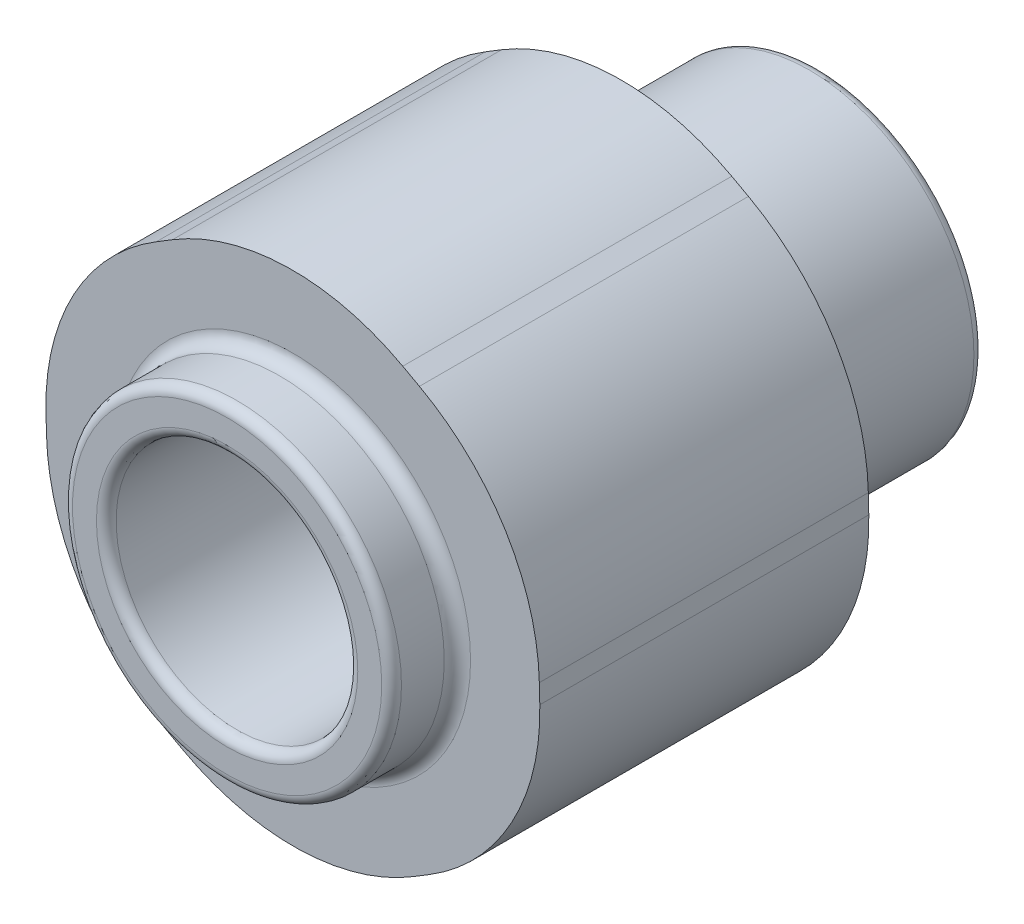
SolidWorks part; units mm, degrees
material "moto_orange"
ref_plane "Front Plane" through (0, 0, 0) normal (0, 0, 1) x (1, 0, 0)
ref_plane "Top Plane" through (0, 0, 0) normal (0, 1, 0) x (1, 0, 0)
ref_plane "Right Plane" through (0, 0, 0) normal (1, 0, 0) x (0, 0, -1)
sketch "Sketch1" plane through (0, 0, 0) normal (0, 0, 1) x (1, 0, 0)
  line L1 (7.3935, 4.5096) -> (-0.2087, 8.6577)
  line L2 (-0.2087, 8.6577) -> (-7.6022, 4.1482)
  line L3 (-7.6022, 4.1482) -> (-7.3935, -4.5096)
  line L4 (-7.3935, -4.5096) -> (0.2087, -8.6577)
  line L5 (0.2087, -8.6577) -> (7.6022, -4.1482)
  line L6 (7.6022, -4.1482) -> (7.3935, 4.5096)
  circle A0 centre (0, 0) radius 7.5 construction
  dimension "D1" = 15
extrude "Boss-Extrude1" add sketch "Sketch1" along normal blind 10
sketch "Sketch2" plane through (0, 0, 0) normal (0, 0, -1) x (-1, 0, 0)
  circle A0 centre (0, 0) radius 5
  dimension "D1" = 10
extrude "Boss-Extrude2" add sketch "Sketch2" along normal blind 6
fillet "Fillet1" radius 0.4 1 edges at (-5, 0, 0)
sketch "Sketch3" plane through (0, 0, 10) normal (0, 0, 1) x (1, 0, 0)
  circle A0 centre (0, 0) radius 5
  dimension "D1" = 10
extrude "Boss-Extrude3" add sketch "Sketch3" along normal blind 2
fillet "Fillet3" radius 0.4 1 edges at (5, 0, 10)
sketch "Sketch4" plane through (0, 0, 12) normal (0, 0, 1) x (1, 0, 0)
  circle A0 centre (0, 0) radius 3.672
extrude "Cut-Extrude1" cut sketch "Sketch4" against normal blind 18
fillet "Fillet4" radius 0.3 4 edges at (3.672, 0, -6) (-5, 0, -6) (3.672, 0, 12) (5, 0, 12)
fillet "Fillet5" radius 7 6 edges at (7.3935, 4.5096, 5) (7.6022, -4.1482, 5) (0.2087, -8.6577, 5) (-7.3935, -4.5096, 5) (-7.6022, 4.1482, 5) (-0.2087, 8.6577, 5)
